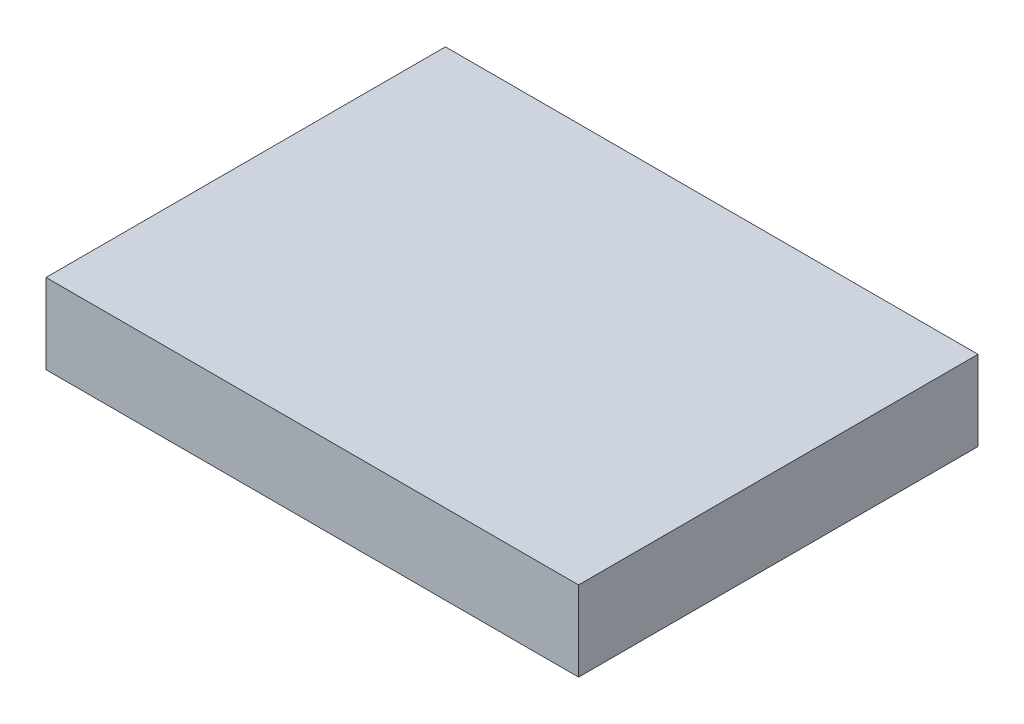
SolidWorks part; units mm, degrees
ref_plane "Front Plane" through (0, 0, 0) normal (0, 0, 1) x (1, 0, 0)
ref_plane "Top Plane" through (0, 0, 0) normal (0, 1, 0) x (1, 0, 0)
ref_plane "Right Plane" through (0, 0, 0) normal (1, 0, 0) x (0, 0, -1)
sketch "Sketch1" plane through (0, 0, 0) normal (0, 1, 0) x (1, 0, 0)
  line L0 (-254, 190.5) -> (254, -190.5) construction
  line L1 (-254, 190.5) -> (254, 190.5)
  line L2 (-254, 190.5) -> (-254, -190.5)
  line L3 (-254, -190.5) -> (254, -190.5)
  line L4 (254, 190.5) -> (254, -190.5)
  dimension "D1" = 508
  dimension "D2" = 381
extrude "Boss-Extrude1" add sketch "Sketch1" along normal blind 76.2
